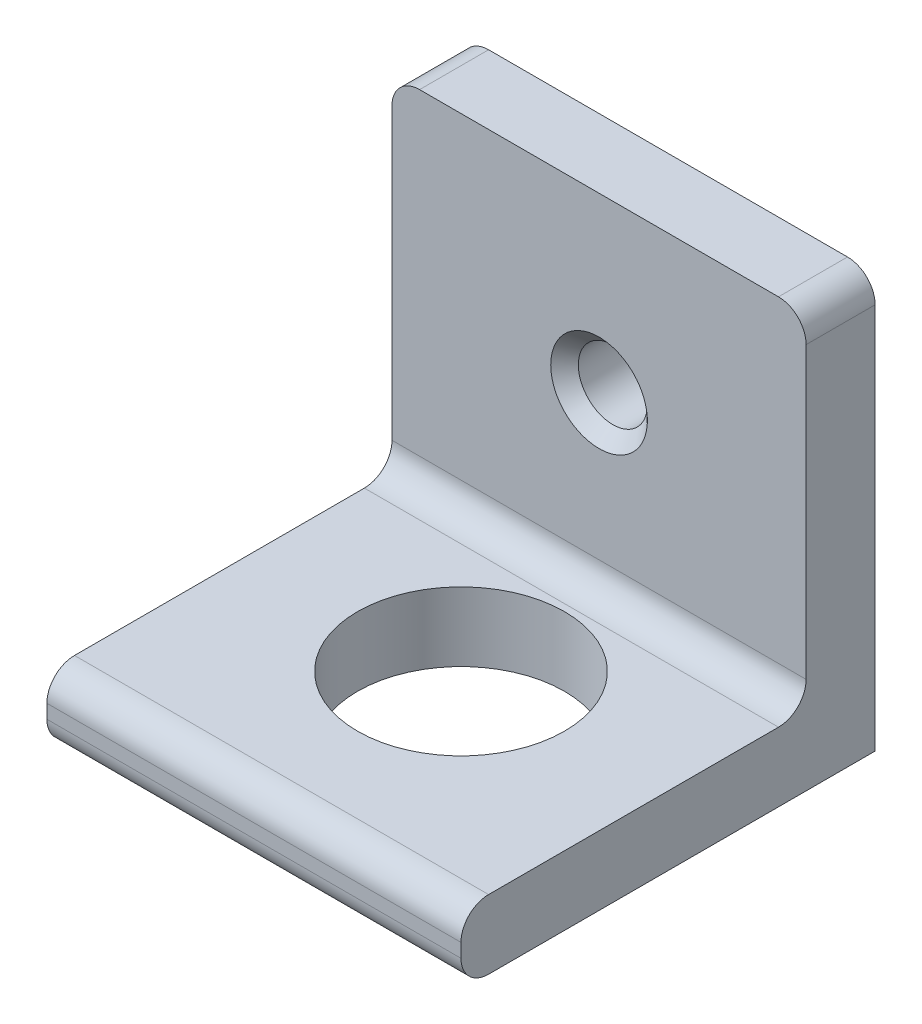
SolidWorks part; units mm, degrees
ref_plane "Front Plane" through (0, 0, 0) normal (0, 0, 1) x (1, 0, 0)
ref_plane "Top Plane" through (0, 0, 0) normal (0, 1, 0) x (1, 0, 0)
ref_plane "Right Plane" through (0, 0, 0) normal (1, 0, 0) x (0, 0, -1)
sketch "Sketch1" plane through (0, 0, 0) normal (0, 1, 0) x (1, 0, 0)
  line L1 (-52.6912, -15.8157) -> (97.3088, -15.8157)
  line L2 (-52.6912, -15.8157) -> (-52.6912, 14.1843)
  line L3 (-52.6912, 14.1843) -> (97.3088, 14.1843)
  line L4 (97.3088, -15.8157) -> (97.3088, 14.1843)
  dimension "D1" = 30
  dimension "D2" = 150
extrude "Boss-Extrude1" add sketch "Sketch1" along normal blind 5
sketch "Sketch3" plane through (0, 5, 0) normal (0, 1, 0) x (1, 0, 0)
  line L0 (97.3088, 14.1843) -> (-52.6912, 14.1843) construction
  line L1 (-52.6912, 14.1843) -> (97.3088, 14.1843)
  line L2 (-52.6912, 14.1843) -> (-52.6912, 9.1843)
  line L3 (-52.6912, 9.1843) -> (97.3088, 9.1843)
  line L4 (97.3088, 14.1843) -> (97.3088, 9.1843)
  line L5 (97.3088, -15.8157) -> (97.3088, 14.1843) construction
  dimension "D1" = 5
  dimension "D2" = 150
extrude "Boss-Extrude2" add sketch "Sketch3" along normal blind 25
ref_plane "Plane1" through (-52.6912, 0, 15.8157) normal (1, 0, 0) x (0, 0, -1)
sketch "Sketch6" plane through (0, 5, 0) normal (0, 1, 0) x (1, 0, 0)
  line L0 (97.3088, 14.1843) -> (-52.6912, 14.1843) construction
  circle A5 centre (82.3088, -0.8157) radius 7.5
  circle A6 centre (54.8088, -8.3157) radius 5
  circle A7 centre (29.8088, -8.3157) radius 5
  circle A8 centre (2.3088, -8.3157) radius 5
  circle A9 centre (-37.6912, -8.3157) radius 5
  dimension "D1" = 15
  dimension "D2" = 15
extrude "Cut-Extrude2" cut sketch "Sketch6" against normal blind 25
sketch "Sketch7" plane through (0, 0, -9.1843) normal (0, 0, 1) x (1, 0, 0)
  line L0 (97.3088, 30) -> (97.3088, 5) construction
  line L1 (-52.6912, 30) -> (-52.6912, 5) construction
  circle A0 centre (82.3088, 17.4787) radius 2.5
  circle A1 centre (-37.6912, 17.4787) radius 2.5
  circle A2 centre (22.3088, 17.4787) radius 2.5
  point P2 (97.3088, 17.5)
  dimension "D1" = 15
  dimension "D2" = 15
extrude "Cut-Extrude3" cut sketch "Sketch7" against normal blind 25
chamfer "Chamfer1" distance 1 angle 45 3 edges at (24.8088, 17.4787, -9.1843) (-35.1912, 17.4787, -9.1843) (84.8088, 17.4787, -9.1843)
fillet "Fillet2" radius 2 5 edges at (22.3088, 5, 15.8157) (22.3088, 0, 15.8157) (-52.6912, 30, -11.6843) (97.3088, 30, -11.6843)
sketch "Sketch8" plane through (-52.6912, 0, 0) normal (-1, 0, 0) x (0, 0, 1)
  line L1 (-21.7913, 40.7682) -> (21.4835, 40.7682)
  line L2 (-21.7913, 40.7682) -> (-21.7913, -23.8452)
  line L3 (-21.7913, -23.8452) -> (21.4835, -23.8452)
  line L4 (21.4835, 40.7682) -> (21.4835, -23.8452)
extrude "Cut-Extrude4" cut sketch "Sketch8" against normal blind 120
fillet "Fillet3" radius 2 1 edges at (67.3088, 30, -11.6843)
